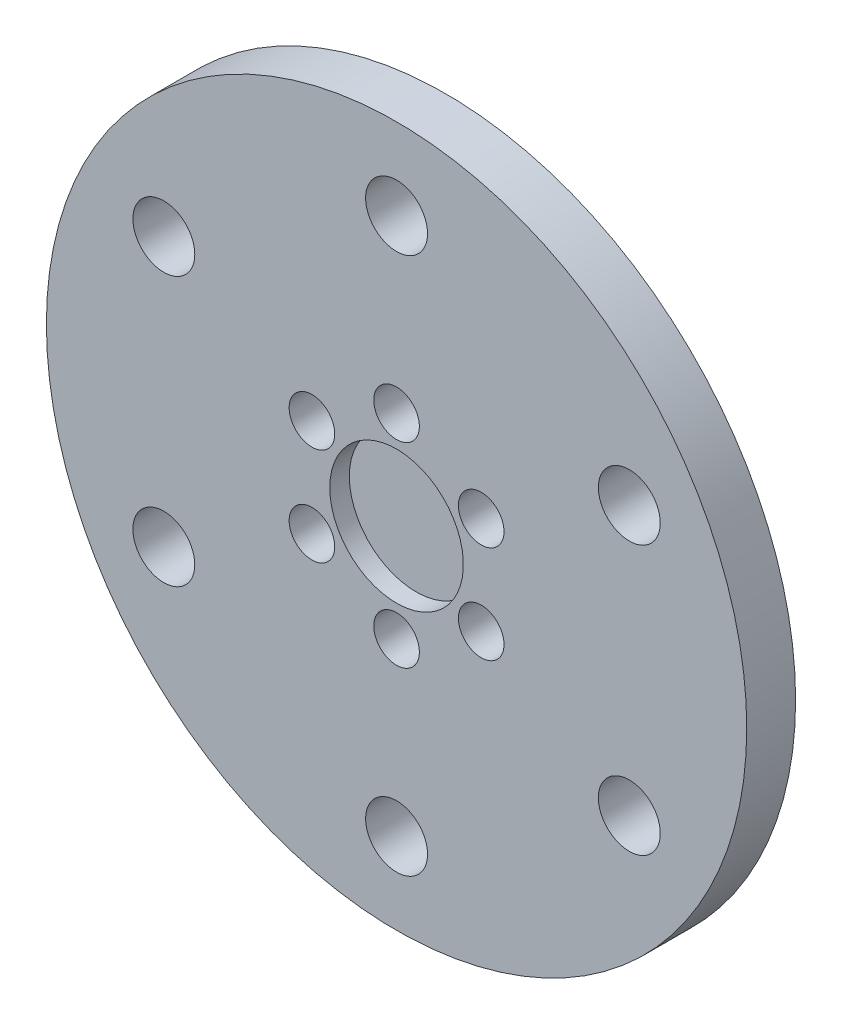
SolidWorks part; units mm, degrees
ref_plane "正面" through (0, 0, 0) normal (0, 0, 1) x (1, 0, 0)
ref_plane "平面" through (0, 0, 0) normal (0, 1, 0) x (1, 0, 0)
ref_plane "右側面" through (0, 0, 0) normal (1, 0, 0) x (0, 0, -1)
sketch "ｽｹｯﾁ1" plane through (0, 0, 0) normal (0, 0, 1) x (1, 0, 0)
  circle A0 centre (0, 0) radius 21.5
  dimension "D1" = 43
extrude "ﾎﾞｽ - 押し出し1" add sketch "ｽｹｯﾁ1" along normal blind 3
sketch "ｽｹｯﾁ2" plane through (0, 0, 0) normal (0, 0, 1) x (1, 0, 0)
  circle A0 centre (0, 0) radius 6 construction
  circle A1 centre (0, 6) radius 1.4
  circle A2 centre (5.1962, 3) radius 1.4
  circle A3 centre (5.1962, -3) radius 1.4
  circle A4 centre (0, -6) radius 1.4
  circle A5 centre (-5.1962, -3) radius 1.4
  circle A6 centre (-5.1962, 3) radius 1.4
  point P6 (-10.0875, -1.679)
  point P7 (0, 0)
  point P17 (0, 0)
  dimension "D1" = 12
  dimension "D2" = 2.8
  dimension "D3" = 6
extrude "ｶｯﾄ - 押し出し1" cut sketch "ｽｹｯﾁ2" against normal through all both and the other way through all
sketch "ｽｹｯﾁ3" plane through (0, 0, 3) normal (0, 0, 1) x (1, 0, 0)
  line L0 (0, 16.5) -> (0, 0) construction
  line L1 (0, 0) -> (0, 16.5) construction
  circle A0 centre (0, 0) radius 16.5 construction
  circle A1 centre (0, 16.5) radius 1.9
  circle A2 centre (14.2894, 8.25) radius 1.9
  circle A3 centre (14.2894, -8.25) radius 1.9
  circle A4 centre (0, -16.5) radius 1.9
  circle A5 centre (-14.2894, -8.25) radius 1.9
  circle A6 centre (-14.2894, 8.25) radius 1.9
  point P6 (-15.8702, 3.1039)
  point P7 (0, 0)
  point P18 (0, 0)
  point P19 (0, 0)
  dimension "D2" = 3.8
  dimension "D3" = 33
  dimension "D4" = 6
extrude "ｶｯﾄ - 押し出し2" cut sketch "ｽｹｯﾁ3" against normal through all both and the other way through all
sketch "ｽｹｯﾁ4" plane through (0, 0, 3) normal (0, 0, 1) x (1, 0, 0)
  circle A0 centre (0, 0) radius 4.1
  dimension "D1" = 8.2
extrude "ｶｯﾄ - 押し出し3" cut sketch "ｽｹｯﾁ4" against normal blind 1.2 and the other way through all
